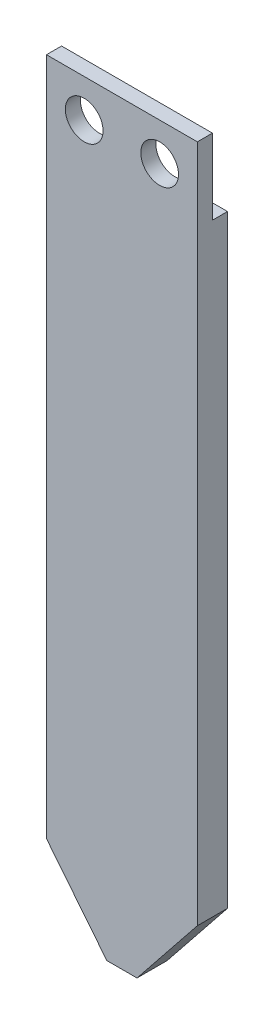
SolidWorks part; units mm, degrees
ref_plane "前视基准面" through (0, 0, 0) normal (0, 0, 1) x (1, 0, 0)
ref_plane "上视基准面" through (0, 0, 0) normal (0, 1, 0) x (1, 0, 0)
ref_plane "右视基准面" through (0, 0, 0) normal (1, 0, 0) x (0, 0, -1)
other "Configuration Table"
sketch "草图1" plane through (0, 0, 0) normal (0, 0, 1) x (1, 0, 0)
  line L1 (0, 0) -> (20, 0)
  line L2 (0, 0) -> (0, -100)
  line L3 (0, -100) -> (20, -100)
  line L4 (20, 0) -> (20, -100)
  dimension "D1" = 100
  dimension "D2" = 20
extrude "凸台-拉伸1" add sketch "草图1" along normal blind 4
sketch "草图2" plane through (0, 0, 4) normal (0, 0, 1) x (1, 0, 0)
  line L0 (20, 0) -> (0, 0) construction
  line L3 (0, 0) -> (0, -100) construction
  line L4 (20, -100) -> (20, 0) construction
  circle A0 centre (5, -5) radius 2.5
  circle A1 centre (15, -5) radius 2.5
  dimension "D3" = 5
  dimension "D1" = 5
  dimension "D2" = 5
  dimension "D4" = 5
extrude "切除-拉伸1" cut sketch "草图2" against normal through all
sketch "草图3" plane through (0, 0, 0) normal (0, 0, -1) x (-1, 0, 0)
  line L0 (-20, -100) -> (-20, 0) construction
  line L1 (0, 0) -> (-20, 0)
  line L2 (0, 0) -> (0, -10)
  line L3 (0, -10) -> (-20, -10)
  line L4 (-20, 0) -> (-20, -10)
  dimension "D1" = 10
extrude "切除-拉伸2" cut sketch "草图3" against normal blind 2
sketch "草图4" plane through (0, 0, 4) normal (0, 0, 1) x (1, 0, 0)
  line L0 (0, -90) -> (0, -100)
  line L1 (0, 0) -> (0, -100) construction
  line L2 (0, -100) -> (8, -100)
  line L3 (0, -100) -> (20, -100) construction
  line L4 (8, -100) -> (0, -90)
  line L5 (10, -90.3607) -> (10, -103.6855) construction
  line L6 (20, -100) -> (12, -100)
  line L7 (20, -90) -> (20, -100)
  line L8 (12, -100) -> (20, -90)
  dimension "D1" = 90
  dimension "D2" = 8
  dimension "D3" = 10
extrude "切除-拉伸3" cut sketch "草图4" against normal through all
